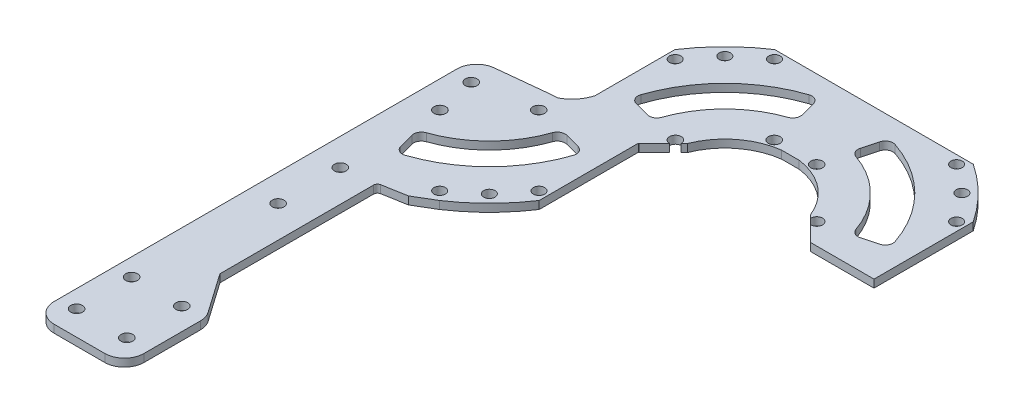
SolidWorks part; units mm, degrees
ref_plane "前视基准面" through (0, 0, 0) normal (0, 0, 1) x (1, 0, 0)
ref_plane "上视基准面" through (0, 0, 0) normal (0, 1, 0) x (1, 0, 0)
ref_plane "右视基准面" through (0, 0, 0) normal (1, 0, 0) x (0, 0, -1)
sketch "Sketch1" plane through (0, 0, 0) normal (0, 1, 0) x (1, 0, 0)
  line L16 (-21.193, -132.0787) -> (-21.193, -166.2197)
  line L18 (-3.6839, -92.5046) -> (-7.5562, -91.467)
  line L19 (-27.3046, -111.2155) -> (-26.267, -115.0878)
  line L28 (-21.7752, -198.4709) -> (-18.2823, -198.4709)
  line L29 (-13.2823, -193.4709) -> (-13.2823, -179.1028)
  line L30 (-14.1854, -176.2366) -> (-21.193, -166.2197)
  line L31 (-21.193, -132.0787) -> (-21.193, -126.2373)
  line L32 (-36.193, -193.4709) -> (-36.193, -90.8303)
  line L34 (-19.3243, -84.5508) -> (-31.7174, -85.8579)
  line L35 (-21.7752, -198.4709) -> (-31.193, -198.4709)
  line L61 (-21.193, -126.2373) -> (-14.3494, -125.0219)
  line L62 (-14.3494, -125.0219) -> (-9.4045, -122.0787)
  line L68 (-12.4964, -84.0822) -> (-19.3243, -84.5508)
  line L69 (3.1036, -84.0822) -> (-12.4964, -84.0822)
  line L71 (3.307, -84.0787) -> (3.307, -109.3671)
  line L72 (3.307, -84.0787) -> (3.1036, -84.0822)
  arc A1 (-9.4045, -122.0787) -> (3.307, -109.3671) centre (-34.693, -84.0787) ccw
  arc A4 (-18.2823, -198.4709) -> (-13.2823, -193.4709) centre (-18.2823, -193.4709) ccw
  arc A5 (-36.193, -90.8303) -> (-31.7174, -85.8579) centre (-31.193, -90.8303) cw
  arc A6 (-36.193, -193.4709) -> (-31.193, -198.4709) centre (-31.193, -193.4709) ccw
  arc A7 (-13.2823, -179.1028) -> (-14.1854, -176.2366) centre (-18.2823, -179.1028) ccw
  circle A63 centre (-18.9192, -192.2044) radius 1.5
  circle A65 centre (-18.9192, -178.2044) radius 1.5
  circle A66 centre (-31.7174, -178.2044) radius 1.5
  circle A67 centre (-31.7174, -192.2044) radius 1.5
  circle A72 centre (-29.2876, -102.069) radius 1.5
  circle A74 centre (-16.7027, -89.4841) radius 1.5
  arc A76 (-23.6978, -116.4659) -> (-2.3058, -95.0739) centre (-34.5331, -84.2386) ccw
  arc A77 (-2.3058, -95.0739) -> (-3.6839, -92.5046) centre (-4.2015, -94.4365) ccw
  arc A78 (-7.5562, -91.467) -> (-9.9638, -92.7446) centre (-8.0739, -93.3989) ccw
  arc A79 (-26.0271, -108.8079) -> (-9.9638, -92.7446) centre (-34.5331, -84.2386) ccw
  arc A80 (-26.0271, -108.8079) -> (-27.3046, -111.2155) centre (-25.3728, -110.6978) ccw
  arc A81 (-26.267, -115.0878) -> (-23.6978, -116.4659) centre (-24.3352, -114.5702) ccw
  circle A82 centre (1.1583, -107.273) radius 1.45
  circle A84 centre (-4.4995, -114.2722) radius 1.45
  circle A86 centre (-11.4987, -119.93) radius 1.45
  circle A98 centre (-29.2876, -127.4625) radius 1.5
  circle A99 centre (-29.2876, -143.3026) radius 1.5
  circle A102 centre (-31.442, -91.9537) radius 1.5
  dimension "D3" = 5
  dimension "D4" = 5
  dimension "D5" = 5
extrude "Boss-Extrude1" add sketch "Sketch1" along normal blind 2
sketch "草图1" plane through (0, 0, 0) normal (0, -1, 0) x (1, 0, 0)
  line L5 (-12.6964, 84.0822) -> (-12.6964, 58.7937)
  line L8 (23.0525, 67.3891) -> (27.5547, 67.3857)
  line L13 (0.0151, 46.0822) -> (25.3036, 46.0822)
  line L15 (7.3439, 80.1765) -> (3.4382, 84.0822)
  line L16 (8.813, 78.7074) -> (9.6445, 77.8759)
  line L17 (63.3036, 58.7937) -> (63.3036, 84.0787)
  line L18 (25.3036, 46.0822) -> (50.592, 46.0822)
  line L19 (52.4403, 76.6938) -> (56.3127, 75.6563)
  line L20 (33.7295, 53.0731) -> (32.6919, 56.9454)
  line L21 (17.9152, 56.9454) -> (16.8777, 53.0731)
  line L22 (-5.7055, 75.6563) -> (-1.8332, 76.6938)
  line L23 (-12.6964, 84.0822) -> (3.4382, 84.0822)
  line L26 (47.1689, 84.0787) -> (43.2633, 80.1731)
  line L27 (41.7942, 78.704) -> (40.9627, 77.8725)
  line L28 (63.3036, 84.0787) -> (47.1689, 84.0787)
  arc A27 (0.0151, 46.0822) -> (-12.6964, 58.7937) centre (25.3036, 84.0822) cw
  arc A29 (63.3036, 58.7937) -> (50.592, 46.0822) centre (25.3036, 84.0822) cw
  circle A30 centre (61.1549, 60.8879) radius 1.45
  circle A31 centre (55.497, 53.8887) radius 1.45
  circle A32 centre (48.4978, 48.2309) radius 1.45
  circle A33 centre (30.7089, 66.0919) radius 1.5
  arc A34 (56.3127, 75.6563) -> (57.6908, 73.087) centre (55.795, 73.7244) cw
  arc A35 (50.0327, 75.4163) -> (52.4403, 76.6938) centre (51.9227, 74.762) cw
  arc A36 (50.0327, 75.4163) -> (33.9695, 59.353) centre (25.4635, 83.9223) cw
  arc A37 (32.6919, 56.9454) -> (33.9695, 59.353) centre (34.6238, 57.4631) cw
  arc A38 (36.2987, 51.695) -> (33.7295, 53.0731) centre (35.6614, 53.5907) cw
  arc A39 (57.6908, 73.087) -> (36.2987, 51.695) centre (25.4635, 83.9223) cw
  circle A41 centre (2.1093, 48.2309) radius 1.45
  circle A42 centre (-4.8899, 53.8887) radius 1.45
  circle A43 centre (-10.5477, 60.8879) radius 1.45
  arc A44 (8.813, 78.7074) -> (7.3439, 80.1765) centre (7.3133, 78.6768) cw
  arc A45 (16.8777, 53.0731) -> (14.3084, 51.695) centre (14.9458, 53.5907) cw
  arc A46 (16.6377, 59.353) -> (17.9152, 56.9454) centre (15.9834, 57.4631) cw
  arc A47 (16.6377, 59.353) -> (0.5744, 75.4163) centre (25.1437, 83.9223) cw
  arc A48 (-1.8332, 76.6938) -> (0.5744, 75.4163) centre (-1.3155, 74.762) cw
  arc A49 (-7.0836, 73.087) -> (-5.7055, 75.6563) centre (-5.1879, 73.7244) cw
  arc A50 (14.3084, 51.695) -> (-7.0836, 73.087) centre (25.1437, 83.9223) cw
  circle A51 centre (19.8982, 66.0919) radius 1.5
  arc A52 (19.0973, 68.4231) -> (23.0525, 67.3891) centre (25.3036, 84.0822) ccw
  arc A54 (9.6445, 77.8759) -> (19.0973, 68.4231) centre (25.3036, 84.0822) ccw
  arc A57 (27.5547, 67.3857) -> (31.5098, 68.4196) centre (25.3036, 84.0787) ccw
  arc A58 (31.5098, 68.4196) -> (40.9627, 77.8725) centre (25.3036, 84.0787) ccw
  arc A59 (41.7942, 78.704) -> (43.2633, 80.1731) centre (43.2939, 78.6734) ccw
extrude "凸台-拉伸1" add sketch "草图1" against normal blind 2
sketch "草图2" plane through (0, 0, 0) normal (0, -1, 0) x (1, 0, 0)
  line L1 (-12.4437, 84.2503) -> (-17.4093, 84.5911)
  line L2 (-12.4437, 77.825) -> (-12.4437, 84.2503)
  arc A0 (-12.4437, 77.825) -> (-17.4093, 84.5911) centre (-20.8202, 76.8827) ccw
extrude "凸台-拉伸2" add sketch "草图2" against normal blind 2
fillet "Fillet1" radius 1 1 edges at (-21.193, 1, 126.2373)
